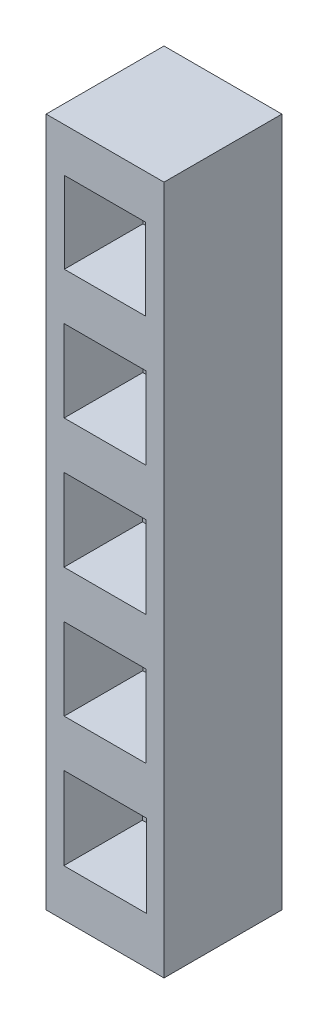
SolidWorks part; units mm, degrees
ref_plane "前视基准面" through (0, 0, 0) normal (0, 0, 1) x (1, 0, 0)
ref_plane "上视基准面" through (0, 0, 0) normal (0, 1, 0) x (1, 0, 0)
ref_plane "右视基准面" through (0, 0, 0) normal (1, 0, 0) x (0, 0, -1)
sketch "草图1" plane through (0, 0, 0) normal (0, 0, 1) x (1, 0, 0)
  line L1 (-7.5, -50) -> (7.5, -50)
  line L2 (-7.5, -50) -> (-7.5, 50)
  line L3 (-7.5, 50) -> (7.5, 50)
  line L4 (7.5, -50) -> (7.5, 50)
  line L5 (-7.5, -50) -> (7.5, 50) construction
  line L6 (-7.5, 50) -> (7.5, -50) construction
  point P0 (0, 0)
  dimension "D1" = 15
  dimension "D2" = 100
extrude "凸台-拉伸1" add sketch "草图1" along normal blind 15
sketch "草图3" plane through (0, 0, 15) normal (0, 0, 1) x (1, 0, 0)
  line L0 (-7.5, -50) -> (7.5, -50) construction
  line L1 (-5.175, 32.1) -> (5.175, 32.1)
  line L2 (-5.175, 32.1) -> (-5.175, 21.75)
  line L3 (-5.175, 21.75) -> (5.175, 21.75)
  line L4 (5.175, 32.1) -> (5.175, 21.75)
  line L5 (-5.175, 32.1) -> (5.175, 21.75) construction
  line L6 (-5.175, 21.75) -> (5.175, 32.1) construction
  line L7 (-5.2, 15.75) -> (5.2, 15.75)
  line L8 (-5.2, 15.75) -> (-5.2, 5.35)
  line L9 (-5.2, 5.35) -> (5.2, 5.35)
  line L10 (5.2, 15.75) -> (5.2, 5.35)
  line L11 (-5.2, 15.75) -> (5.2, 5.35) construction
  line L12 (-5.2, 5.35) -> (5.2, 15.75) construction
  line L13 (-5.225, -0.65) -> (5.225, -0.65)
  line L14 (-5.225, -0.65) -> (-5.225, -11.1)
  line L15 (-5.225, -11.1) -> (5.225, -11.1)
  line L16 (5.225, -0.65) -> (5.225, -11.1)
  line L17 (-5.225, -0.65) -> (5.225, -11.1) construction
  line L18 (-5.225, -11.1) -> (5.225, -0.65) construction
  line L19 (-5.2, -17.1) -> (5.2, -17.1)
  line L20 (-5.2, -17.1) -> (-5.2, -27.5)
  line L21 (-5.2, -27.5) -> (5.2, -27.5)
  line L22 (5.2, -17.1) -> (5.2, -27.5)
  line L23 (-5.2, -17.1) -> (5.2, -27.5) construction
  line L24 (-5.2, -27.5) -> (5.2, -17.1) construction
  line L25 (-5.25, -33.5) -> (5.25, -33.5)
  line L26 (-5.25, -33.5) -> (-5.25, -44)
  line L27 (-5.25, -44) -> (5.25, -44)
  line L28 (5.25, -33.5) -> (5.25, -44)
  line L29 (-5.25, -33.5) -> (5.25, -44) construction
  line L30 (-5.25, -44) -> (5.25, -33.5) construction
  point P0 (0, 26.925)
  point P5 (0, 10.55)
  point P10 (0, -5.875)
  point P15 (0, -22.3)
  point P20 (0, -38.75)
  dimension "D1" = 10.35
  dimension "D2" = 10.35
  dimension "D3" = 10.4
  dimension "D4" = 10.4
  dimension "D5" = 10.45
  dimension "D6" = 10.45
  dimension "D7" = 10.4
  dimension "D8" = 10.4
  dimension "D9" = 10.5
  dimension "D10" = 10.5
  dimension "D11" = 6
  dimension "D12" = 6
  dimension "D13" = 6
  dimension "D14" = 6
  dimension "D15" = 6
extrude "切除-拉伸1" cut sketch "草图3" against normal blind 10
sketch "草图4" plane through (0, 0, 15) normal (0, 0, 1) x (1, 0, 0)
  line L0 (7.5, -50) -> (7.5, 50) construction
  line L1 (-7.5, 50) -> (7.5, 50)
  line L2 (-7.5, 50) -> (-7.5, 37.6832)
  line L3 (-7.5, 37.6832) -> (7.5, 37.6832)
  line L4 (7.5, 50) -> (7.5, 37.6832)
extrude "切除-拉伸2" cut sketch "草图4" against normal through all
